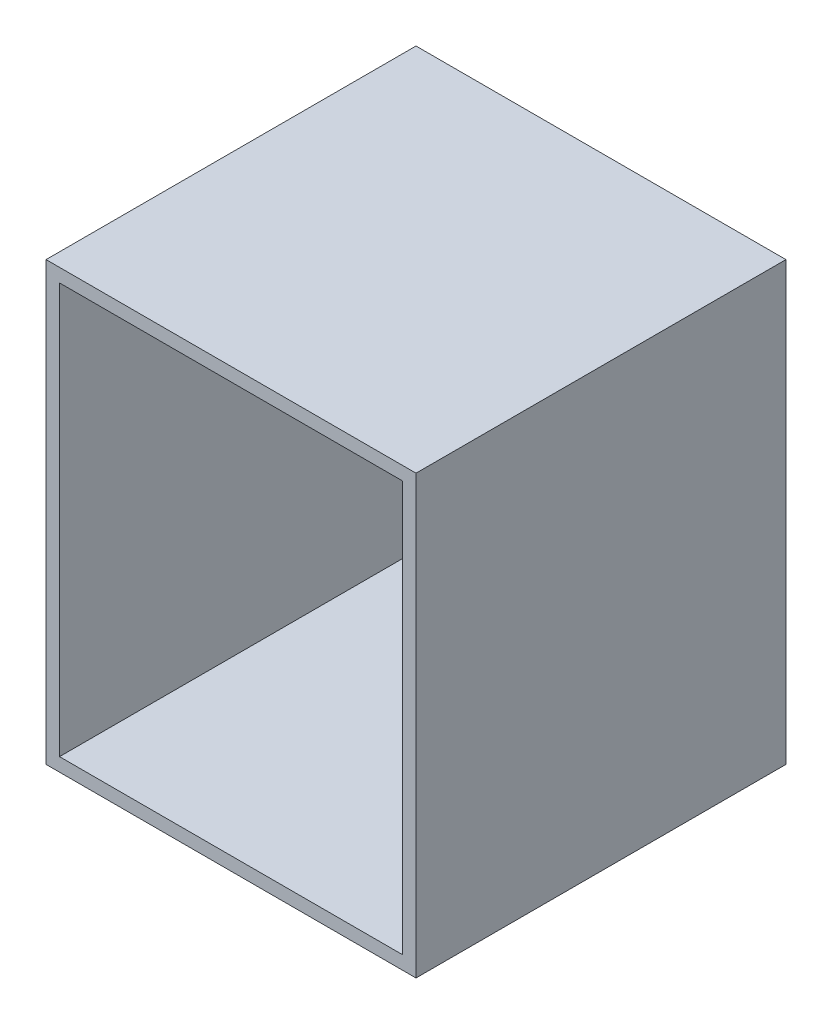
SolidWorks part; units mm, degrees
ref_plane "Front Plane" through (0, 0, 0) normal (0, 0, 1) x (1, 0, 0)
ref_plane "Top Plane" through (0, 0, 0) normal (0, 1, 0) x (1, 0, 0)
ref_plane "Right Plane" through (0, 0, 0) normal (1, 0, 0) x (0, 0, -1)
sketch "Sketch1" plane through (0, 0, 0) normal (0, 0, 1) x (1, 0, 0)
  line L1 (27.5, -32.5) -> (-27.5, -32.5)
  line L2 (27.5, -32.5) -> (27.5, 32.5)
  line L3 (27.5, 32.5) -> (-27.5, 32.5)
  line L4 (-27.5, -32.5) -> (-27.5, 32.5)
  line L5 (27.5, -32.5) -> (-27.5, 32.5) construction
  line L6 (27.5, 32.5) -> (-27.5, -32.5) construction
  point P0 (0, 0)
  dimension "D1" = 55
  dimension "D2" = 65
extrude "Boss-Extrude1" add sketch "Sketch1" along normal mid plane 55
shell "Shell1" thickness 2
sketch "Sketch2" plane through (0, 0, -25.5) normal (0, 0, 1) x (1, 0, 0)
  line L0 (25.5, 30.5) -> (-25.5, 30.5) construction
  line L1 (25.5, 30.5) -> (-25.5, 30.5)
  line L2 (-25.5, 30.5) -> (-25.5, -30.5) construction
  line L3 (-25.5, 30.5) -> (-25.5, -30.5)
  line L4 (25.5, -30.5) -> (25.5, 30.5) construction
  line L5 (25.5, -30.5) -> (25.5, 30.5)
  line L6 (-25.5, -30.5) -> (25.5, -30.5) construction
  line L7 (-25.5, -30.5) -> (25.5, -30.5)
extrude "Cut-Extrude1" cut sketch "Sketch2" against normal through all
